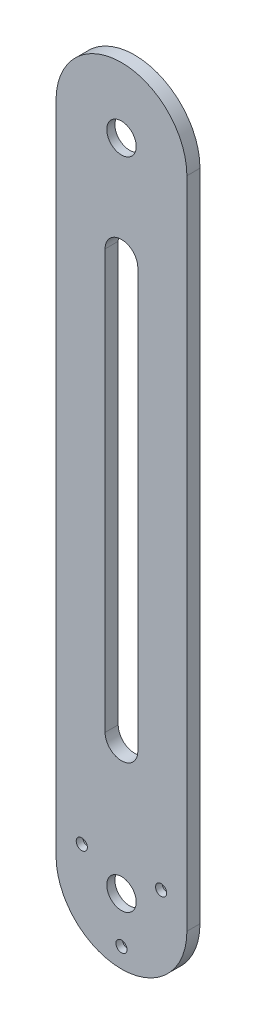
SolidWorks part; units mm, degrees
ref_plane "前视基准面" through (0, 0, 0) normal (0, 0, 1) x (1, 0, 0)
ref_plane "上视基准面" through (0, 0, 0) normal (0, 1, 0) x (1, 0, 0)
ref_plane "右视基准面" through (0, 0, 0) normal (1, 0, 0) x (0, 0, -1)
sketch "草图1" plane through (0, 0, 0) normal (0, 0, 1) x (1, 0, 0)
  line L0 (0, 0) -> (0, -200) construction
  line L3 (-20, 0) -> (-20, -200)
  line L5 (20, -200) -> (20, 0)
  circle A4 centre (0, 0) radius 8.75
  arc A5 (20, 0) -> (-20, 0) centre (0, 0) ccw
  arc A6 (-20, -200) -> (20, -200) centre (0, -200) ccw
  circle A7 centre (0, -200) radius 8.75
  dimension "D1" = 17.5
  dimension "D3" = 200
  dimension "D4" = 40
  dimension "D5" = 17.5
  dimension "D2" = 40
extrude "凸台-拉伸1" add sketch "草图1" along normal blind 4
sketch "草图3" plane through (0, 0, 4) normal (0, 0, 1) x (1, 0, 0)
  circle A0 centre (0, 0) radius 8.75 construction
  circle A1 centre (0, 0) radius 8.75
  circle A2 centre (0, 0) radius 4.5
  circle A3 centre (0, -200) radius 8.75 construction
  circle A4 centre (0, -200) radius 8.75
  circle A5 centre (0, -200) radius 4.5
  dimension "D1" = 9
  dimension "D2" = 9
extrude "凸台-拉伸2" add sketch "草图3" against normal blind 2.5
sketch "草图2" plane through (0, 0, 4) normal (0, 0, 1) x (1, 0, 0)
  line L13 (-5, 0) -> (-5, -200)
  line L14 (5, -200) -> (5, 0)
  line L15 (-5, -31.845) -> (-5, -159.845)
  line L16 (5, -159.845) -> (5, -31.845)
  arc A3 (-5, -31.845) -> (5, -31.845) centre (0, -31.845) cw
  arc A8 (-5, -200) -> (5, -200) centre (0, -200) ccw
  arc A10 (-5, -159.845) -> (5, -159.845) centre (0, -159.845) ccw
  dimension "D1" = 15
extrude "切除-拉伸2" cut sketch "草图2" against normal through all
sketch "草图4" plane through (0, 0, 0) normal (0, 0, -1) x (-1, 0, 0)
  line L0 (0, -200) -> (0, -214) construction
  line L1 (0, -200) -> (12.1244, -193) construction
  circle A0 centre (0, -200) radius 14 construction
  circle A1 centre (0, -214) radius 1.7
  circle A2 centre (-12.1244, -193) radius 1.7
  circle A3 centre (12.1244, -193) radius 1.7
  point P11 (0, -200)
  dimension "D1" = 28
  dimension "D2" = 3.4
  dimension "D5" = 7
  dimension "D4" = 120
  dimension "D3" = 3
extrude "切除-拉伸3" cut sketch "草图4" against normal through all
sketch "草图5" plane through (0, 0, 0) normal (0, 0, -1) x (-1, 0, 0)
  circle A0 centre (-12.1244, -193) radius 3
  circle A1 centre (12.1244, -193) radius 3
  circle A2 centre (0, -214) radius 3
  dimension "D1" = 6
  dimension "D2" = 6
  dimension "D3" = 6
extrude "切除-拉伸4" cut sketch "草图5" against normal blind 2
